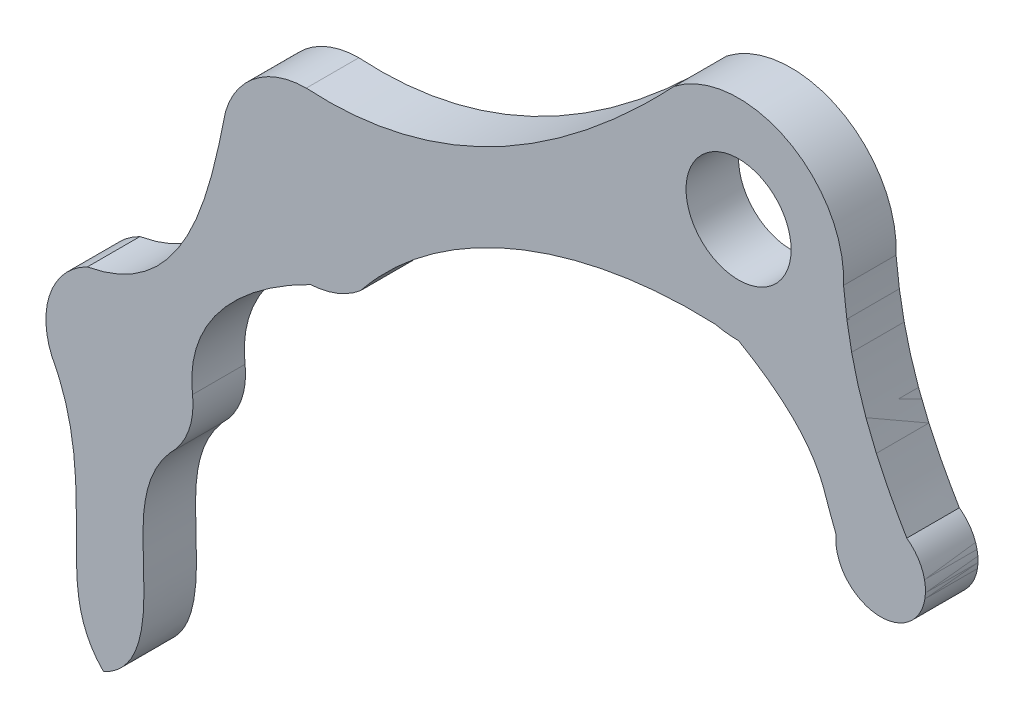
SolidWorks part; units mm, degrees
ref_plane "Alzado" through (0, 0, 0) normal (0, 0, 1) x (1, 0, 0)
ref_plane "Planta" through (0, 0, 0) normal (0, 1, 0) x (1, 0, 0)
ref_plane "Vista lateral" through (0, 0, 0) normal (1, 0, 0) x (0, 0, -1)
ref_plane "Plano1" through (0, 0, 0) normal (0, 0, -1) x (-1, 0, 0)
sketch "Croquis1" plane through (0, 0, 0) normal (0, 0, -1) x (-1, 0, 0)
  circle A0 centre (0, 0) radius 5
  arc A1 (65.3666, -43.9226) -> (61.9752, -34.9056) centre (58.9168, -41.2021) ccw
  arc A2 (48.8157, -15.5017) -> (41.1378, -9.7489) centre (41.1378, -17.7489) ccw
  arc A3 (6.1317, 7.8995) -> (-9.9899, -0.4489) centre (0, 0) ccw
  arc A5 (0, -10) -> (2.2269, -9.7489) centre (0, 0) ccw
  arc A6 (35.9788, -23.8632) -> (40.7273, -25.7384) centre (41.1378, -17.7489) ccw
  arc A7 (51.9608, -40.4192) -> (54.1304, -46.3099) centre (58.9168, -41.2021) ccw
  arc A8 (-9.274, -21.3129) -> (-16.0086, -18.2669) centre (-13.5206, -21.734) ccw
  spline S0 degree 3 poles (48.8157, -15.5017) (50.329, -23.0829) (52.396, -33.1575) (61.9752, -34.9056) knots 0 0 0 0 1 1 1 1
  spline S1 degree 3 poles (6.1317, 7.8995) (15.14, -1.6562) (27.2451, -10.6659) (41.1378, -9.7489) knots 0 0 0 0 1 1 1 1
  spline S2 degree 3 poles (-16.0086, -18.2669) (-15.7977, -17.8958) (-12.2626, -11.8712) (-10.5466, -6.5812) (-9.9899, -0.4489) knots 0 0 0 0 0.040395 0.656611 0.656611 0.656611 0.656611
  spline S3 degree 3 poles (0, -10) (-2.9267, -11.6868) (-7.5134, -15.0007) (-8.6736, -19.9407) (-9.274, -21.3129) knots 0 0 0 0 0.464305 0.659665 0.659665 0.659665 0.659665
  spline S4 degree 3 poles (35.9788, -23.8632) (28.0581, -13.941) (14.6752, -9.2056) (2.2269, -9.7489) knots 0 0 0 0 1 1 1 1
  spline S5 degree 3 poles (51.9608, -40.4192) (52.8003, -33.4878) (46.1444, -28.3742) (40.7273, -25.7384) knots 0 0 0 0 1 1 1 1
  spline S6 degree 3 poles (60.43, -67.4924) (57.1033, -65.9041) (55.9168, -57.6089) (57.45, -50.2015) (54.1304, -46.3099) knots 0 0 0 0 0.425583 1 1 1 1
  spline S7 degree 3 poles (65.3666, -43.9226) (62.9488, -48.3768) (63.0282, -56.4383) (63.0358, -64.9071) (60.43, -67.4924) knots 0 0 0 0 0.588886 1 1 1 1
extrude "Saliente-Extruir1" add sketch "Croquis1" against normal blind 5
sketch "Croquis2" plane through (0, 0, 5) normal (0, 0, 1) x (1, 0, 0)
  circle A2 centre (13.5206, -21.734) radius 4.2674
extrude "Saliente-Extruir2" add sketch "Croquis2" against normal blind 5
sketch "Croquis3" plane through (0, 0, 5) normal (0, 0, 1) x (1, 0, 0)
  arc A0 (9.274, -21.3129) -> (16.0086, -18.2669) centre (13.5206, -21.734) ccw construction
  arc A1 (9.274, -21.3129) -> (16.0086, -18.2669) centre (13.5206, -21.734) ccw
  spline S0 degree 3 poles (-181.6394, 1988.541) (121.7917, 29.5802) (-65.3038, 45.122) (57.7503, -64.6038) (-1963.185, 266.4953) knots -5.791561 -5.791561 -5.791561 -5.791561 0.616216 2.782297 2.782297 2.782297 2.782297 only from (9.9899, -0.4489) to (16.0086, -18.2669) construction
  spline S1 degree 3 poles (1881.2523, 681.4109) (-44.22, -92.0635) (122.2302, 54.5608) (-231.2586, -45.5568) (1999.8052, 6.6816) knots -2.82471 -2.82471 -2.82471 -2.82471 0.195359 5.301154 5.301154 5.301154 5.301154 only from (9.274, -21.3129) to (0, -10) construction
  spline S2 degree 3 poles (9.9899, -0.4489) (10.5466, -6.5812) (12.2626, -11.8712) (15.7977, -17.8958) (16.0086, -18.2669) knots 0 0 0 0 0.616216 0.656611 0.656611 0.656611 0.656611
  spline S3 degree 3 poles (9.274, -21.3129) (8.6736, -19.9407) (7.5134, -15.0007) (2.9267, -11.6868) (0, -10) knots 0 0 0 0 0.195359 0.659665 0.659665 0.659665 0.659665
surface "Superficie-Extruir1" sketch "Croquis3" parameters "D1"=5
